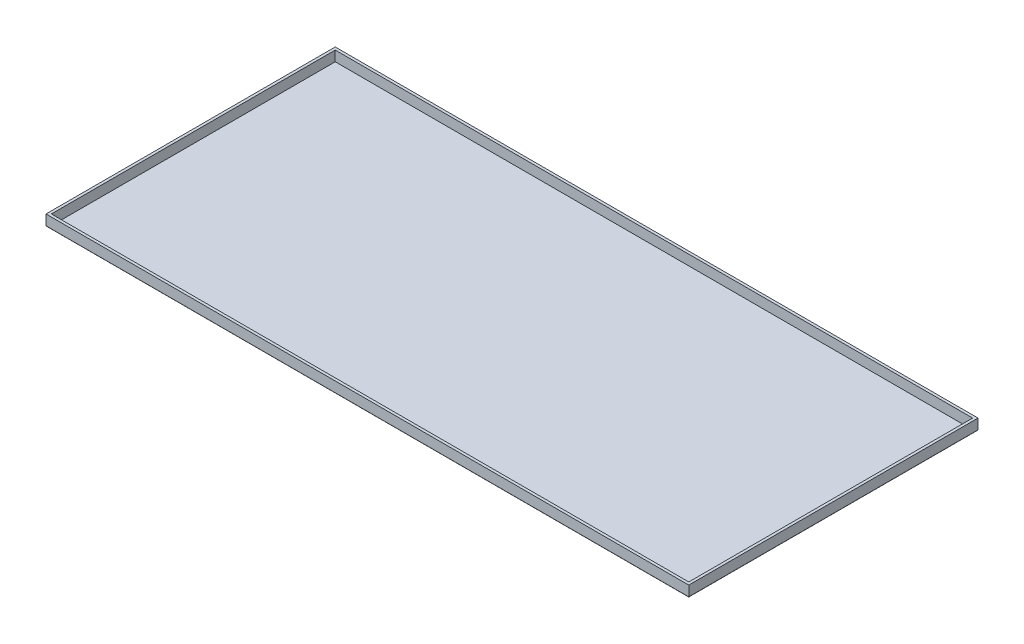
SolidWorks part; units mm, degrees
ref_plane "Front Plane" through (0, 0, 0) normal (0, 0, 1) x (1, 0, 0)
ref_plane "Top Plane" through (0, 0, 0) normal (0, 1, 0) x (1, 0, 0)
ref_plane "Right Plane" through (0, 0, 0) normal (1, 0, 0) x (0, 0, -1)
sketch "Sketch2" plane through (0, 0, 0) normal (0, 1, 0) x (1, 0, 0)
  line L0 (297.5, -132.5) -> (-297.5, -132.5)
  line L1 (300, -135) -> (-300, -135)
  line L2 (300, -135) -> (300, 135)
  line L3 (300, 135) -> (-300, 135)
  line L4 (-300, -135) -> (-300, 135)
  line L5 (300, -135) -> (-300, 135) construction
  line L6 (300, 135) -> (-300, -135) construction
  line L7 (297.5, -132.5) -> (297.5, 132.5)
  line L8 (297.5, 132.5) -> (-297.5, 132.5)
  line L9 (-297.5, -132.5) -> (-297.5, 132.5)
  line L10 (297.5, -132.5) -> (-297.5, 132.5) construction
  line L11 (297.5, 132.5) -> (-297.5, -132.5) construction
  point P0 (0, 0)
  point P6 (0, 0)
  point P11 (0, 0)
  dimension "D1" = 270
  dimension "D2" = 600
  dimension "D3" = 265
  dimension "D4" = 595
extrude "Boss-Extrude2" add sketch "Sketch2" along normal blind 10
sketch "Sketch3" plane through (0, 0, 0) normal (0, 1, 0) x (1, 0, 0)
  line L1 (297.5, -132.5) -> (-297.5, -132.5)
  line L2 (297.5, -132.5) -> (297.5, 132.5)
  line L3 (297.5, 132.5) -> (-297.5, 132.5)
  line L4 (-297.5, -132.5) -> (-297.5, 132.5)
  line L5 (297.5, -132.5) -> (-297.5, 132.5) construction
  line L6 (297.5, 132.5) -> (-297.5, -132.5) construction
  point P0 (0, 0)
  dimension "D1" = 265
  dimension "D2" = 595
extrude "Boss-Extrude3" add sketch "Sketch3" along normal blind 0.5
fillet "Fillet1" radius 0.5 4 edges at (-300, 0, 0) (0, 0, -135) (300, 0, 0) (0, 0, 135)
